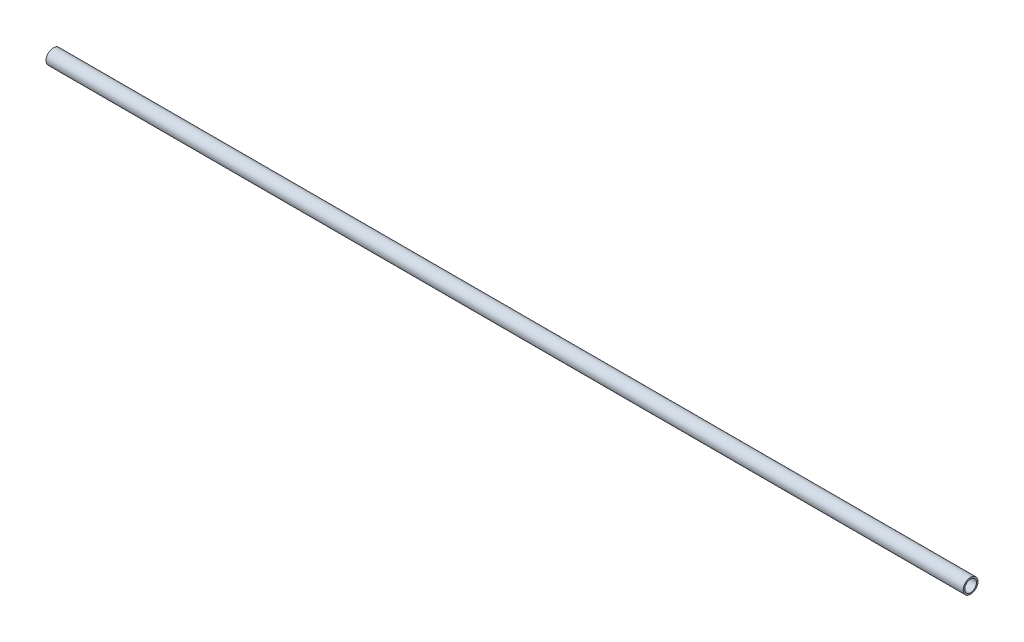
SolidWorks part; units mm, degrees
ref_plane "Front Plane" through (0, 0, 0) normal (0, 0, 1) x (1, 0, 0)
ref_plane "Top Plane" through (0, 0, 0) normal (0, 1, 0) x (1, 0, 0)
ref_plane "Right Plane" through (0, 0, 0) normal (1, 0, 0) x (0, 0, -1)
sketch "Sketch2" plane through (0, 0, 0) normal (1, 0, 0) x (0, 0, -1)
  circle A0 centre (0, 0) radius 8.05
  circle A1 centre (0, 0) radius 6.4
  dimension "D1" = 12.8
  dimension "D2" = 16.1
extrude "Boss-Extrude1" add sketch "Sketch2" along normal blind 1000
